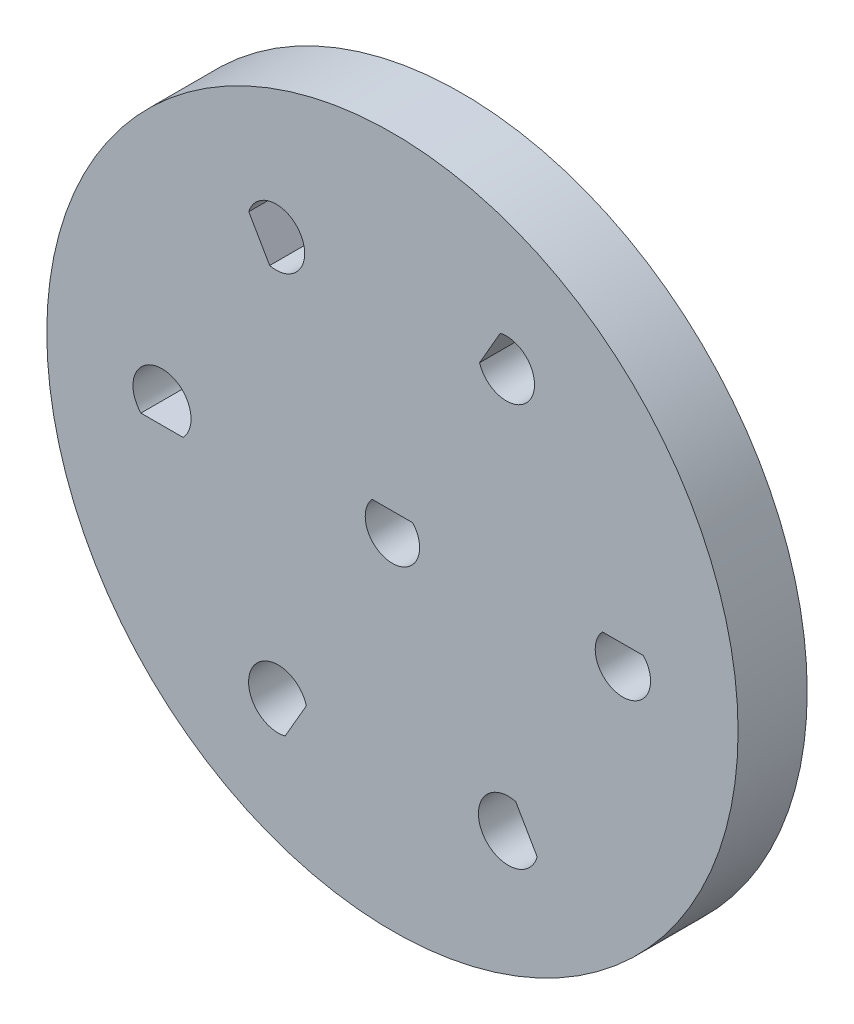
SolidWorks part; units mm, degrees
ref_plane "Front Plane" through (0, 0, 0) normal (0, 0, 1) x (1, 0, 0)
ref_plane "Top Plane" through (0, 0, 0) normal (0, 1, 0) x (1, 0, 0)
ref_plane "Right Plane" through (0, 0, 0) normal (1, 0, 0) x (0, 0, -1)
sketch "Sketch1" plane through (0, 0, 0) normal (0, 0, 1) x (1, 0, 0)
  line L0 (1.118, 1) -> (-1.118, 1)
  line L1 (13.8292, 1.0167) -> (11.5708, 1.0167)
  line L2 (5.9429, 12.4552) -> (4.8027, 10.4804)
  line L3 (-7.9173, 11.3279) -> (-6.7662, 9.3341)
  line L4 (-13.8619, -1.2569) -> (-11.5381, -1.2569)
  line L5 (-5.9154, -12.6984) -> (-4.7428, -10.6674)
  line L6 (7.977, -11.5203) -> (6.7938, -9.471)
  circle A0 centre (0, 0) radius 19.05
  arc A1 (-1.118, 1) -> (1.118, 1) centre (0, 0) ccw
  arc A2 (11.5708, 1.0167) -> (13.8292, 1.0167) centre (12.7, -0.0083) ccw
  arc A3 (4.8027, 10.4804) -> (5.9429, 12.4552) centre (6.2821, 10.9428) ccw
  arc A4 (-6.7662, 9.3341) -> (-7.9173, 11.3279) centre (-6.4108, 10.8685) ccw
  arc A5 (-11.5381, -1.2569) -> (-13.8619, -1.2569) centre (-12.7, -0.1569) ccw
  arc A6 (-4.7428, -10.6674) -> (-5.9154, -12.6984) centre (-6.3034, -11.1204) ccw
  arc A7 (6.7938, -9.471) -> (7.977, -11.5203) centre (6.3895, -11.0706) ccw
  point P25 (0, -0.0949)
  dimension "D1" = 38.1
  dimension "D3" = 3
  dimension "D5" = 2.55
  dimension "D4" = 1.525
  dimension "D6" = 1.55
  dimension "D7" = 1.575
  dimension "D8" = 1.6
  dimension "D9" = 1.625
  dimension "D10" = 1.65
  dimension "D14" = 2.75
  dimension "D2" = 2.5
  dimension "D11" = 2.6
  dimension "D12" = 2.65
  dimension "D13" = 2.7
  dimension "D15" = 2.8
extrude "Boss-Extrude1" add sketch "Sketch1" along normal blind 3.81
